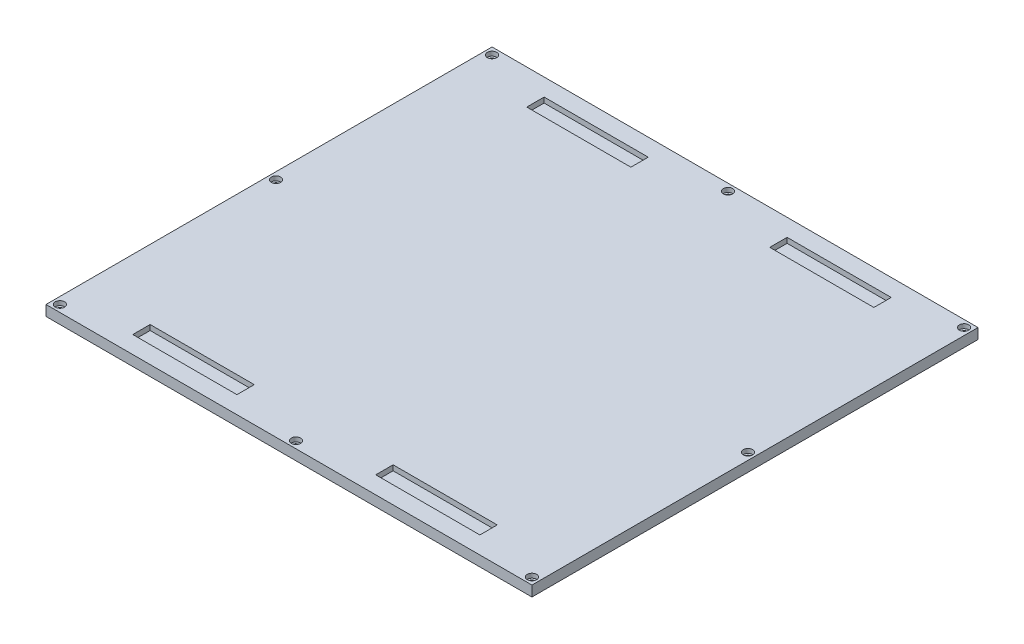
SolidWorks part; units mm, degrees
ref_plane "Front Plane" through (0, 0, 0) normal (0, 0, 1) x (1, 0, 0)
ref_plane "Top Plane" through (0, 0, 0) normal (0, 1, 0) x (1, 0, 0)
ref_plane "Right Plane" through (0, 0, 0) normal (1, 0, 0) x (0, 0, -1)
sketch "Sketch1" plane through (0, 0, 0) normal (0, 1, 0) x (1, 0, 0)
  line L1 (0, 0) -> (280, 0)
  line L2 (0, 0) -> (0, 257)
  line L3 (0, 257) -> (280, 257)
  line L4 (280, 0) -> (280, 257)
  dimension "D1" = 280
  dimension "D2" = 257
extrude "Boss-Extrude2" add sketch "Sketch1" along normal blind 6
sketch "Sketch3" plane through (0, 6, 0) normal (0, 1, 0) x (1, 0, 0)
  line L0 (0, 0) -> (4.0022, 4.0022) construction
  line L1 (0, 257) -> (4.0022, 252.9978) construction
  line L2 (280, 257) -> (275.9978, 252.9978) construction
  line L3 (280, 0) -> (275.9978, 4.0022) construction
  line L4 (4.0022, 252.9978) -> (275.9978, 252.9978) construction
  line L5 (275.9978, 252.9978) -> (275.9978, 4.0022) construction
  line L6 (275.9978, 4.0022) -> (4.0022, 4.0022) construction
  line L7 (4.0022, 252.9978) -> (4.0022, 4.0022) construction
  line L10 (275.9978, 128.5) -> (280, 128.5) construction
  line L11 (280, 0) -> (280, 257) construction
  circle A0 centre (4.0022, 252.9978) radius 1.45
  circle A1 centre (275.9978, 252.9978) radius 1.45
  circle A2 centre (4.0022, 4.0022) radius 1.45
  circle A3 centre (275.9978, 4.0022) radius 1.45
  circle A4 centre (4.0022, 128.5) radius 1.45
  circle A5 centre (275.9978, 128.5) radius 1.45
  circle A6 centre (140, 4.0022) radius 1.45
  circle A7 centre (140, 252.9978) radius 1.45
  dimension "D3" = 2.9
  dimension "D4" = 2.9
  dimension "D5" = 2.9
  dimension "D6" = 2.9
  dimension "D7" = 2.9
  dimension "D8" = 2.9
  dimension "D9" = 2.9
  dimension "D10" = 2.9
  dimension "D1" = 5.66
  dimension "D2" = 4.0022
extrude "Cut-Extrude1" cut sketch "Sketch3" against normal through all
sketch "Sketch4" plane through (0, 6, 0) normal (0, 1, 0) x (1, 0, 0)
  circle A0 centre (4.0022, 4.0022) radius 2.7
  circle A1 centre (4.0022, 252.9978) radius 2.7
  circle A2 centre (275.9978, 252.9978) radius 2.7
  circle A3 centre (275.9978, 4.0022) radius 2.7
  circle A4 centre (4.0022, 128.5) radius 2.7
  circle A5 centre (275.9978, 128.5) radius 2.7
  circle A6 centre (140, 252.9978) radius 2.7
  circle A7 centre (140, 4.0022) radius 2.7
  dimension "D1" = 5.4
  dimension "D2" = 5.4
  dimension "D3" = 5.4
  dimension "D4" = 5.4
  dimension "D5" = 5.4
  dimension "D6" = 5.4
  dimension "D7" = 5.4
  dimension "D8" = 5.4
extrude "Cut-Extrude4" cut sketch "Sketch4" against normal blind 2.5
sketch "Sketch8" plane through (0, 6, 0) normal (0, 1, 0) x (1, 0, 0)
  line L0 (0, 0) -> (280, 0) construction
  line L1 (70, 247) -> (40, 247) construction
  line L2 (210, 247) -> (240, 247) construction
  line L5 (40, 247) -> (100, 247)
  line L6 (280, 0) -> (140, 0) construction
  line L8 (140, 0) -> (0, 0) construction
  line L9 (140, 0) -> (0, 0) construction
  line L10 (0, 0) -> (70, 0) construction
  line L11 (70, 0) -> (70, 9.9975) construction
  line L12 (140, 0) -> (280, 0) construction
  line L13 (280, 0) -> (210, 0) construction
  line L14 (210, 0) -> (210, 9.9975) construction
  line L15 (70, 9.9975) -> (40, 9.9975) construction
  line L16 (210, 9.9975) -> (240, 9.9975) construction
  line L17 (40, 9.9975) -> (100, 9.9975)
  line L18 (40, 9.9975) -> (40, 19.9975)
  line L19 (40, 19.9975) -> (100, 19.9975)
  line L20 (100, 9.9975) -> (100, 19.9975)
  line L21 (70, 257) -> (70, 247) construction
  line L22 (240, 9.9975) -> (180, 9.9975)
  line L23 (240, 9.9975) -> (240, 19.9975)
  line L24 (240, 19.9975) -> (180, 19.9975)
  line L25 (180, 9.9975) -> (180, 19.9975)
  line L26 (280, 257) -> (0, 257) construction
  line L27 (210, 257) -> (210, 247) construction
  line L28 (40, 247) -> (40, 237)
  line L29 (40, 237) -> (100, 237)
  line L30 (100, 247) -> (100, 237)
  line L31 (240, 247) -> (180, 247)
  line L32 (240, 247) -> (240, 237)
  line L33 (240, 237) -> (180, 237)
  line L34 (180, 247) -> (180, 237)
  dimension "D1" = 30
  dimension "D2" = 60
  dimension "D3" = 10
  dimension "D4" = 30
  dimension "D5" = 10
  dimension "D6" = 60
  dimension "D7" = 10
  dimension "D8" = 10
  dimension "D9" = 30
  dimension "D10" = 30
  dimension "D11" = 60
  dimension "D12" = 10
  dimension "D13" = 60
  dimension "D14" = 10
extrude "Cut-Extrude5" cut sketch "Sketch8" against normal blind 3
